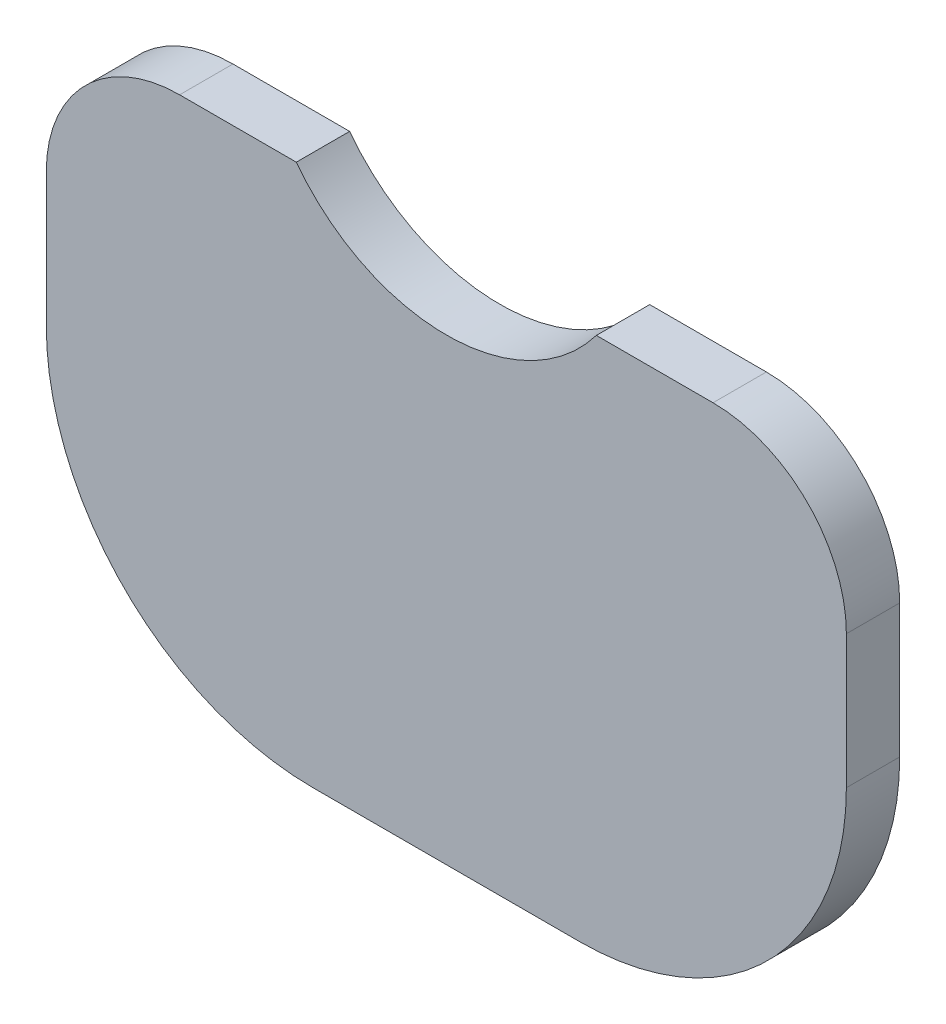
SolidWorks part; units mm, degrees
ref_plane "前视基准面" through (0, 0, 0) normal (0, 0, 1) x (1, 0, 0)
ref_plane "上视基准面" through (0, 0, 0) normal (0, 1, 0) x (1, 0, 0)
ref_plane "右视基准面" through (0, 0, 0) normal (1, 0, 0) x (0, 0, -1)
other "Configuration Table"
sketch "草图1" plane through (0, 0, 0) normal (0, 0, 1) x (1, 0, 0)
  line L1 (10, -20) -> (-10, -20)
  line L2 (30, 0) -> (30, 10)
  line L3 (20, 20) -> (-20, 20)
  line L4 (-30, 0) -> (-30, 10)
  line L5 (30, -20) -> (-30, 20) construction
  line L6 (30, 20) -> (-30, -20) construction
  arc A0 (-30, 10) -> (-20, 20) centre (-20, 10) cw
  arc A1 (30, 10) -> (20, 20) centre (20, 10) ccw
  circle A4 centre (0, 28.5) radius 14.1
  arc A5 (30, 0) -> (10, -20) centre (10, 0) cw
  arc A6 (-10, -20) -> (-30, 0) centre (-10, 0) cw
  point P0 (0, 0)
  dimension "D3" = 10
  dimension "D4" = 28.2
  dimension "D6" = 20
  dimension "D1" = 60
  dimension "D2" = 40
  dimension "D5" = 8.5
extrude "凸台-拉伸1" add sketch "草图1" along normal blind 4 contours A6 L1 A5 L2 A1 L3 A4 A0 L4
sketch "草图3" plane through (0, 0, 0) normal (0, 0, 1) x (1, 0, 0)
  line L0 (20, 20) -> (11.2499, 20) construction
  line L1 (0, 14.4) -> (0, -20) construction
  line L2 (10, -20) -> (-10, -20) construction
  circle A0 centre (-12.5, 0) radius 7.5
  circle A1 centre (12.5, 0) radius 7.5
  arc A2 (-11.2499, 20) -> (11.2499, 20) centre (0, 28.5) ccw construction
  dimension "D1" = 15
  dimension "D2" = 15
  dimension "D3" = 20
  dimension "D4" = 12.5
  dimension "D5" = 12.5
extrude "凸台-拉伸2" add sketch "草图3" against normal blind 6.5
